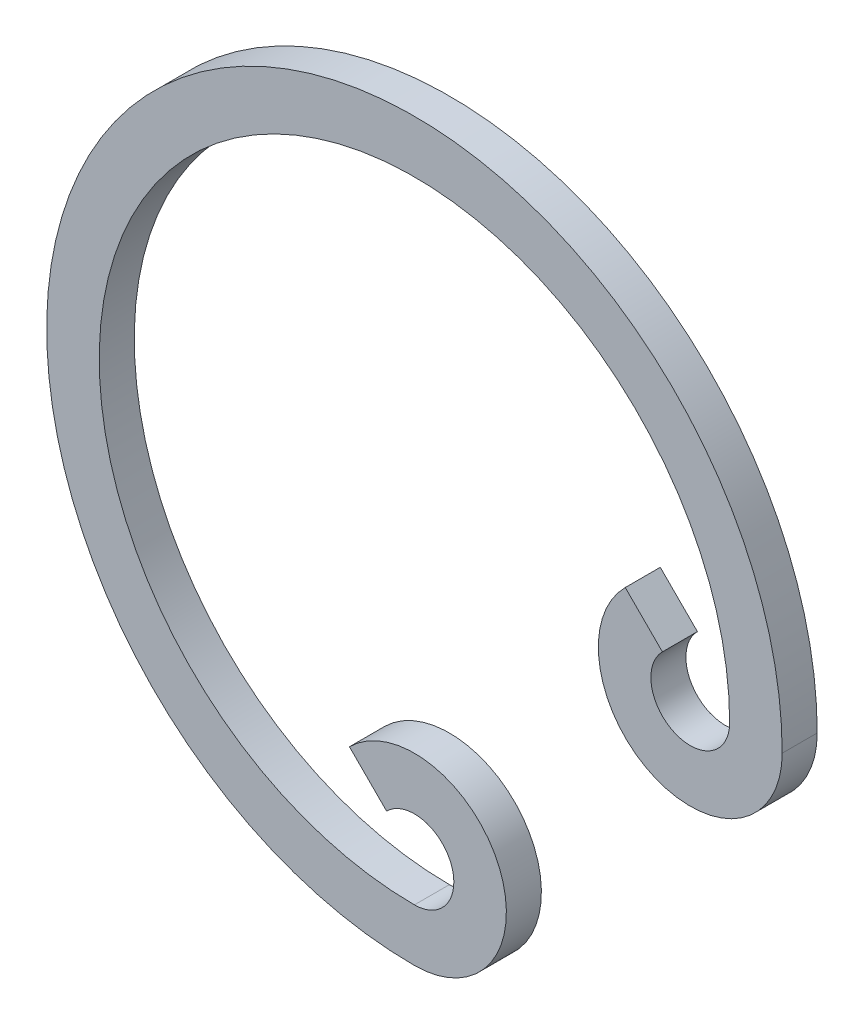
SolidWorks part; units mm, degrees
ref_plane "Alzado" through (0, 0, 0) normal (0, 0, 1) x (1, 0, 0)
ref_plane "Planta" through (0, 0, 0) normal (0, 1, 0) x (1, 0, 0)
ref_plane "Vista lateral" through (0, 0, 0) normal (1, 0, 0) x (0, 0, -1)
sketch "Croquis1" plane through (0, 0, 0) normal (0, 0, 1) x (1, 0, 0)
  line L7 (-0.7955, -7.0795) -> (-1.8562, -6.0188)
  line L11 (-6.364, 6.364) -> (-7.4246, 7.4246)
  arc A0 (-7.4246, 7.4246) -> (0, -10.5) centre (0, 0) ccw
  arc A1 (-6.364, 6.364) -> (0, -9) centre (0, 0) ccw
  arc A2 (0, -10.5) -> (-1.8562, -6.0188) centre (0, -7.875) ccw
  arc A3 (0, -9) -> (-0.7955, -7.0795) centre (0, -7.875) ccw
extrude "Saliente-Extruir1" add sketch "Croquis1" along normal blind 1
mirror "Simetría1" about plane through (-6.364, 6.364, 1) normal (-0.7071, -0.7071, 0) of "Saliente-Extruir1"
